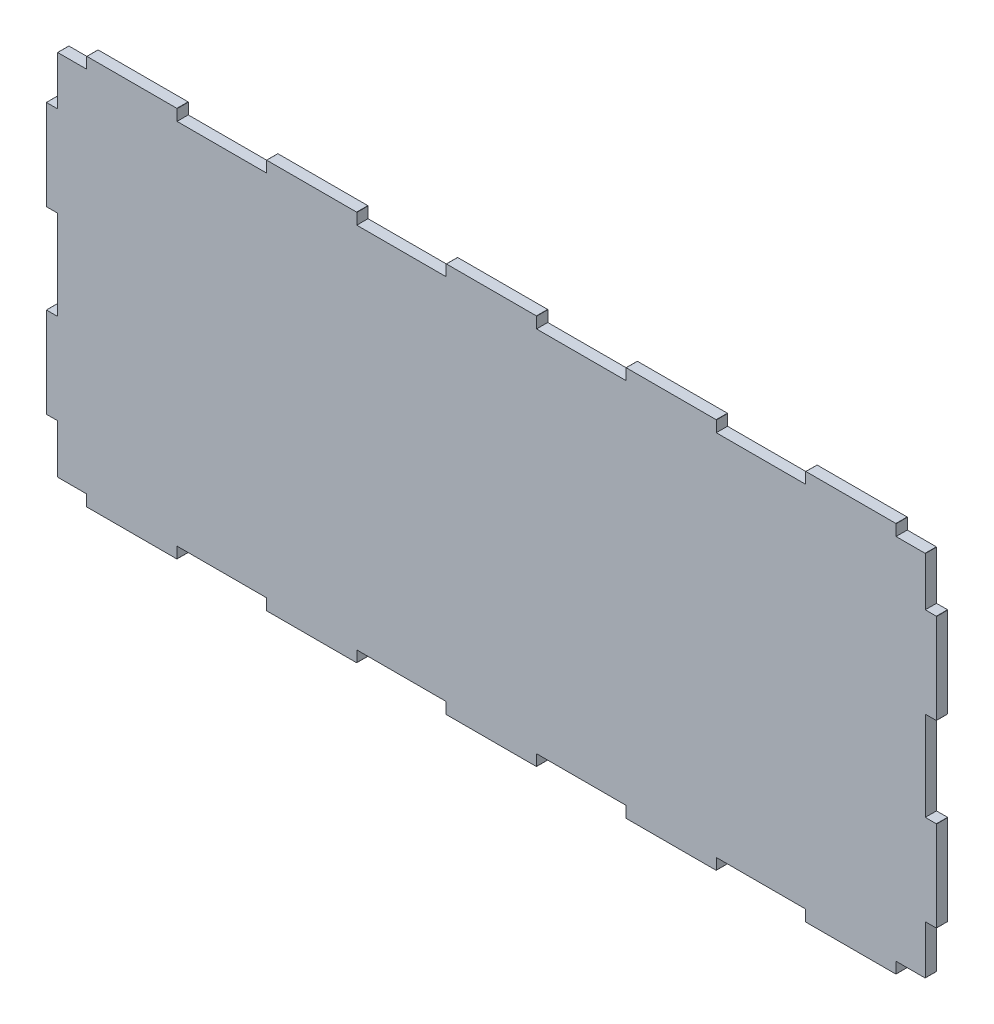
SolidWorks part; units mm, degrees
material "Acrylic (Medium-high impact)"
ref_plane "Front Plane" through (0, 0, 0) normal (0, 0, 1) x (1, 0, 0)
ref_plane "Top Plane" through (0, 0, 0) normal (0, 1, 0) x (1, 0, 0)
ref_plane "Right Plane" through (0, 0, 0) normal (1, 0, 0) x (0, 0, -1)
sketch "Model" plane through (0, 0, 0) normal (0, 0, 1) x (1, 0, 0)
  line L0 (-139.94, -86.83) -> (-139.93, -86.82)
  line L1 (-139.93, -86.82) -> (-139.92, -86.8)
  line L2 (-139.92, -86.8) -> (-139.91, -86.79)
  line L3 (-139.91, -86.79) -> (-139.9, -86.77)
  line L4 (-139.9, -86.77) -> (-139.9, -81.85)
  line L5 (-139.9, -81.85) -> (-100.1, -81.85)
  line L6 (-100.1, -81.85) -> (-100.1, -86.77)
  line L7 (-100.1, -86.77) -> (-100.08, -86.81)
  line L8 (-100.08, -86.81) -> (-100.07, -86.82)
  line L9 (-100.07, -86.82) -> (-100.05, -86.83)
  line L10 (-100.05, -86.83) -> (-100.04, -86.84)
  line L11 (-100.04, -86.84) -> (-100.02, -86.85)
  line L12 (-100.02, -86.85) -> (-59.98, -86.85)
  line L13 (-59.98, -86.85) -> (-59.94, -86.83)
  line L14 (-59.94, -86.83) -> (-59.93, -86.82)
  line L15 (-59.93, -86.82) -> (-59.92, -86.8)
  line L16 (-59.92, -86.8) -> (-59.91, -86.79)
  line L17 (-59.91, -86.79) -> (-59.9, -86.77)
  line L18 (-59.9, -86.77) -> (-59.9, -81.85)
  line L19 (-59.9, -81.85) -> (-20.1, -81.85)
  line L20 (-20.1, -81.85) -> (-20.1, -86.77)
  line L21 (-20.1, -86.77) -> (-20.08, -86.81)
  line L22 (-20.08, -86.81) -> (-20.07, -86.82)
  line L23 (-20.07, -86.82) -> (-20.05, -86.83)
  line L24 (-20.05, -86.83) -> (-20.04, -86.84)
  line L25 (-20.04, -86.84) -> (-20.02, -86.85)
  line L26 (-20.02, -86.85) -> (20.02, -86.85)
  line L27 (20.02, -86.85) -> (20.06, -86.83)
  line L28 (20.06, -86.83) -> (20.07, -86.82)
  line L29 (20.07, -86.82) -> (20.08, -86.8)
  line L30 (20.08, -86.8) -> (20.09, -86.79)
  line L31 (20.09, -86.79) -> (20.1, -86.77)
  line L32 (20.1, -86.77) -> (20.1, -81.85)
  line L33 (20.1, -81.85) -> (59.9, -81.85)
  line L34 (59.9, -81.85) -> (59.9, -86.77)
  line L35 (59.9, -86.77) -> (59.92, -86.81)
  line L36 (59.92, -86.81) -> (59.93, -86.82)
  line L37 (59.93, -86.82) -> (59.95, -86.83)
  line L38 (59.95, -86.83) -> (59.96, -86.84)
  line L39 (59.96, -86.84) -> (59.98, -86.85)
  line L40 (59.98, -86.85) -> (100.02, -86.85)
  line L41 (100.02, -86.85) -> (100.06, -86.83)
  line L42 (100.06, -86.83) -> (100.07, -86.82)
  line L43 (100.07, -86.82) -> (100.08, -86.8)
  line L44 (100.08, -86.8) -> (100.09, -86.79)
  line L45 (100.09, -86.79) -> (100.1, -86.77)
  line L46 (100.1, -86.77) -> (100.1, -81.85)
  line L47 (100.1, -81.85) -> (139.9, -81.85)
  line L48 (139.9, -81.85) -> (139.9, -86.77)
  line L49 (139.9, -86.77) -> (139.92, -86.81)
  line L50 (139.92, -86.81) -> (139.93, -86.82)
  line L51 (139.93, -86.82) -> (139.95, -86.83)
  line L52 (139.95, -86.83) -> (139.96, -86.84)
  line L53 (139.96, -86.84) -> (139.98, -86.85)
  line L54 (139.98, -86.85) -> (180.02, -86.85)
  line L55 (180.02, -86.85) -> (180.06, -86.83)
  line L56 (180.06, -86.83) -> (180.07, -86.82)
  line L57 (180.07, -86.82) -> (180.08, -86.8)
  line L58 (180.08, -86.8) -> (180.09, -86.79)
  line L59 (180.09, -86.79) -> (180.1, -86.77)
  line L60 (180.1, -86.77) -> (180.1, -81.85)
  line L61 (180.1, -81.85) -> (193.02, -81.85)
  line L62 (193.02, -81.85) -> (193.06, -81.83)
  line L63 (193.06, -81.83) -> (193.07, -81.82)
  line L64 (193.07, -81.82) -> (193.08, -81.8)
  line L65 (193.08, -81.8) -> (193.09, -81.79)
  line L66 (193.09, -81.79) -> (193.1, -81.77)
  line L67 (193.1, -81.77) -> (193.1, -60.1)
  line L68 (193.1, -60.1) -> (198.02, -60.1)
  line L69 (198.02, -60.1) -> (198.06, -60.08)
  line L70 (198.06, -60.08) -> (198.07, -60.07)
  line L71 (198.07, -60.07) -> (198.08, -60.05)
  line L72 (198.08, -60.05) -> (198.09, -60.04)
  line L73 (198.09, -60.04) -> (198.1, -60.02)
  line L74 (198.1, -60.02) -> (198.1, -19.98)
  line L75 (198.1, -19.98) -> (198.08, -19.94)
  line L76 (198.08, -19.94) -> (198.07, -19.93)
  line L77 (198.07, -19.93) -> (198.05, -19.92)
  line L78 (198.05, -19.92) -> (198.04, -19.91)
  line L79 (198.04, -19.91) -> (198.02, -19.9)
  line L80 (198.02, -19.9) -> (193.1, -19.9)
  line L81 (193.1, -19.9) -> (193.1, 19.9)
  line L82 (193.1, 19.9) -> (198.02, 19.9)
  line L83 (198.02, 19.9) -> (198.06, 19.92)
  line L84 (198.06, 19.92) -> (198.07, 19.93)
  line L85 (198.07, 19.93) -> (198.08, 19.95)
  line L86 (198.08, 19.95) -> (198.09, 19.96)
  line L87 (198.09, 19.96) -> (198.1, 19.98)
  line L88 (198.1, 19.98) -> (198.1, 60.02)
  line L89 (198.1, 60.02) -> (198.08, 60.06)
  line L90 (198.08, 60.06) -> (198.07, 60.07)
  line L91 (198.07, 60.07) -> (198.05, 60.08)
  line L92 (198.05, 60.08) -> (198.04, 60.09)
  line L93 (198.04, 60.09) -> (198.02, 60.1)
  line L94 (198.02, 60.1) -> (193.1, 60.1)
  line L95 (193.1, 60.1) -> (193.1, 81.77)
  line L96 (193.1, 81.77) -> (193.08, 81.81)
  line L97 (193.08, 81.81) -> (193.07, 81.82)
  line L98 (193.07, 81.82) -> (193.05, 81.83)
  line L99 (193.05, 81.83) -> (193.04, 81.84)
  line L100 (193.04, 81.84) -> (193.02, 81.85)
  line L101 (193.02, 81.85) -> (180.1, 81.85)
  line L102 (180.1, 81.85) -> (180.1, 86.77)
  line L103 (180.1, 86.77) -> (180.08, 86.81)
  line L104 (180.08, 86.81) -> (180.07, 86.82)
  line L105 (180.07, 86.82) -> (180.05, 86.83)
  line L106 (180.05, 86.83) -> (180.04, 86.84)
  line L107 (180.04, 86.84) -> (180.02, 86.85)
  line L108 (180.02, 86.85) -> (139.98, 86.85)
  line L109 (139.98, 86.85) -> (139.94, 86.83)
  line L110 (139.94, 86.83) -> (139.93, 86.82)
  line L111 (139.93, 86.82) -> (139.92, 86.8)
  line L112 (139.92, 86.8) -> (139.91, 86.79)
  line L113 (139.91, 86.79) -> (139.9, 86.77)
  line L114 (139.9, 86.77) -> (139.9, 81.85)
  line L115 (139.9, 81.85) -> (100.1, 81.85)
  line L116 (100.1, 81.85) -> (100.1, 86.77)
  line L117 (100.1, 86.77) -> (100.08, 86.81)
  line L118 (100.08, 86.81) -> (100.07, 86.82)
  line L119 (100.07, 86.82) -> (100.05, 86.83)
  line L120 (100.05, 86.83) -> (100.04, 86.84)
  line L121 (100.04, 86.84) -> (100.02, 86.85)
  line L122 (100.02, 86.85) -> (59.98, 86.85)
  line L123 (59.98, 86.85) -> (59.94, 86.83)
  line L124 (59.94, 86.83) -> (59.93, 86.82)
  line L125 (59.93, 86.82) -> (59.92, 86.8)
  line L126 (59.92, 86.8) -> (59.91, 86.79)
  line L127 (59.91, 86.79) -> (59.9, 86.77)
  line L128 (59.9, 86.77) -> (59.9, 81.85)
  line L129 (59.9, 81.85) -> (20.1, 81.85)
  line L130 (20.1, 81.85) -> (20.1, 86.77)
  line L131 (20.1, 86.77) -> (20.08, 86.81)
  line L132 (20.08, 86.81) -> (20.07, 86.82)
  line L133 (20.07, 86.82) -> (20.05, 86.83)
  line L134 (20.05, 86.83) -> (20.04, 86.84)
  line L135 (20.04, 86.84) -> (20.02, 86.85)
  line L136 (20.02, 86.85) -> (-20.02, 86.85)
  line L137 (-20.02, 86.85) -> (-20.06, 86.83)
  line L138 (-20.06, 86.83) -> (-20.07, 86.82)
  line L139 (-20.07, 86.82) -> (-20.08, 86.8)
  line L140 (-20.08, 86.8) -> (-20.09, 86.79)
  line L141 (-20.09, 86.79) -> (-20.1, 86.77)
  line L142 (-20.1, 86.77) -> (-20.1, 81.85)
  line L143 (-20.1, 81.85) -> (-59.9, 81.85)
  line L144 (-59.9, 81.85) -> (-59.9, 86.77)
  line L145 (-59.9, 86.77) -> (-59.92, 86.81)
  line L146 (-59.92, 86.81) -> (-59.93, 86.82)
  line L147 (-59.93, 86.82) -> (-59.95, 86.83)
  line L148 (-59.95, 86.83) -> (-59.96, 86.84)
  line L149 (-59.96, 86.84) -> (-59.98, 86.85)
  line L150 (-59.98, 86.85) -> (-100.02, 86.85)
  line L151 (-100.02, 86.85) -> (-100.06, 86.83)
  line L152 (-100.06, 86.83) -> (-100.07, 86.82)
  line L153 (-100.07, 86.82) -> (-100.08, 86.8)
  line L154 (-100.08, 86.8) -> (-100.09, 86.79)
  line L155 (-100.09, 86.79) -> (-100.1, 86.77)
  line L156 (-100.1, 86.77) -> (-100.1, 81.85)
  line L157 (-100.1, 81.85) -> (-139.9, 81.85)
  line L158 (-139.9, 81.85) -> (-139.9, 86.77)
  line L159 (-139.9, 86.77) -> (-139.92, 86.81)
  line L160 (-139.92, 86.81) -> (-139.93, 86.82)
  line L161 (-139.93, 86.82) -> (-139.95, 86.83)
  line L162 (-139.95, 86.83) -> (-139.96, 86.84)
  line L163 (-139.96, 86.84) -> (-139.98, 86.85)
  line L164 (-139.98, 86.85) -> (-180.02, 86.85)
  line L165 (-180.02, 86.85) -> (-180.06, 86.83)
  line L166 (-180.06, 86.83) -> (-180.07, 86.82)
  line L167 (-180.07, 86.82) -> (-180.08, 86.8)
  line L168 (-180.08, 86.8) -> (-180.09, 86.79)
  line L169 (-180.09, 86.79) -> (-180.1, 86.77)
  line L170 (-180.1, 86.77) -> (-180.1, 81.85)
  line L171 (-180.1, 81.85) -> (-193.02, 81.85)
  line L172 (-193.02, 81.85) -> (-193.06, 81.83)
  line L173 (-193.06, 81.83) -> (-193.07, 81.82)
  line L174 (-193.07, 81.82) -> (-193.08, 81.8)
  line L175 (-193.08, 81.8) -> (-193.09, 81.79)
  line L176 (-193.09, 81.79) -> (-193.1, 81.77)
  line L177 (-193.1, 81.77) -> (-193.1, 60.1)
  line L178 (-193.1, 60.1) -> (-198.02, 60.1)
  line L179 (-198.02, 60.1) -> (-198.06, 60.08)
  line L180 (-198.06, 60.08) -> (-198.07, 60.07)
  line L181 (-198.07, 60.07) -> (-198.08, 60.05)
  line L182 (-198.08, 60.05) -> (-198.09, 60.04)
  line L183 (-198.09, 60.04) -> (-198.1, 60.02)
  line L184 (-198.1, 60.02) -> (-198.1, 19.98)
  line L185 (-198.1, 19.98) -> (-198.08, 19.94)
  line L186 (-198.08, 19.94) -> (-198.07, 19.93)
  line L187 (-198.07, 19.93) -> (-198.05, 19.92)
  line L188 (-198.05, 19.92) -> (-198.04, 19.91)
  line L189 (-198.04, 19.91) -> (-198.02, 19.9)
  line L190 (-198.02, 19.9) -> (-193.1, 19.9)
  line L191 (-193.1, 19.9) -> (-193.1, -19.9)
  line L192 (-193.1, -19.9) -> (-198.02, -19.9)
  line L193 (-198.02, -19.9) -> (-198.06, -19.92)
  line L194 (-198.06, -19.92) -> (-198.07, -19.93)
  line L195 (-198.07, -19.93) -> (-198.08, -19.95)
  line L196 (-198.08, -19.95) -> (-198.09, -19.96)
  line L197 (-198.09, -19.96) -> (-198.1, -19.98)
  line L198 (-198.1, -19.98) -> (-198.1, -60.02)
  line L199 (-198.1, -60.02) -> (-198.08, -60.06)
  line L200 (-198.08, -60.06) -> (-198.07, -60.07)
  line L201 (-198.07, -60.07) -> (-198.05, -60.08)
  line L202 (-198.05, -60.08) -> (-198.04, -60.09)
  line L203 (-198.04, -60.09) -> (-198.02, -60.1)
  line L204 (-198.02, -60.1) -> (-193.1, -60.1)
  line L205 (-193.1, -60.1) -> (-193.1, -81.77)
  line L206 (-193.1, -81.77) -> (-193.08, -81.81)
  line L207 (-193.08, -81.81) -> (-193.07, -81.82)
  line L208 (-193.07, -81.82) -> (-193.05, -81.83)
  line L209 (-193.05, -81.83) -> (-193.04, -81.84)
  line L210 (-193.04, -81.84) -> (-193.02, -81.85)
  line L211 (-193.02, -81.85) -> (-180.1, -81.85)
  line L212 (-180.1, -81.85) -> (-180.1, -86.77)
  line L213 (-180.1, -86.77) -> (-180.08, -86.81)
  line L214 (-180.08, -86.81) -> (-180.07, -86.82)
  line L215 (-180.07, -86.82) -> (-180.05, -86.83)
  line L216 (-180.05, -86.83) -> (-180.04, -86.84)
  line L217 (-180.04, -86.84) -> (-180.02, -86.85)
  line L218 (-180.02, -86.85) -> (-139.98, -86.85)
  line L219 (-139.98, -86.85) -> (-139.94, -86.83)
extrude "Boss-Extrude1" add sketch "Model" along normal blind 5
